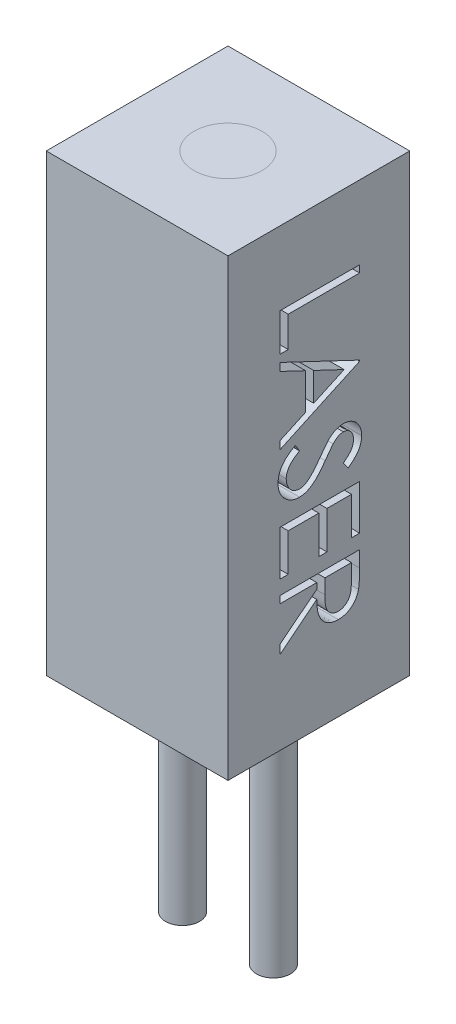
SolidWorks part; units mm, degrees
ref_plane "Front Plane" through (0, 0, 0) normal (0, 0, 1) x (1, 0, 0)
ref_plane "Top Plane" through (0, 0, 0) normal (0, 1, 0) x (1, 0, 0)
ref_plane "Right Plane" through (0, 0, 0) normal (1, 0, 0) x (0, 0, -1)
sketch "Sketch1" plane through (0, 0, 0) normal (0, 0, 1) x (1, 0, 0)
  line L0 (0, -55) -> (0, 55) construction
  line L1 (-4, 20) -> (4, 20)
  line L2 (-4, 20) -> (-4, 0)
  line L3 (-4, 0) -> (4, 0)
  line L4 (4, 20) -> (4, 0)
  line L5 (-4, 20) -> (4, 0) construction
  line L6 (-4, 0) -> (4, 20) construction
  line L7 (55, 0) -> (-55, 0) construction
  point P0 (0, 10)
  dimension "D1" = 20
  dimension "D2" = 8
extrude "Boss-Extrude1" add sketch "Sketch1" along normal blind 8
sketch "Sketch2" plane through (0, 0, 0) normal (0, -1, 0) x (1, 0, 0)
  line L0 (0, -4.4) -> (0, 4.4) construction
  line L1 (4, 8) -> (4, 0) construction
  circle A0 centre (-2, 4) radius 0.75
  circle A1 centre (2, 4) radius 0.75
  point P9 (4, 4)
  dimension "D1" = 1.5
  dimension "D2" = 2
  dimension "D3" = 2
extrude "Boss-Extrude2" add sketch "Sketch2" along normal blind 10
sketch "Sketch3" plane through (0, 20, 0) normal (0, 1, 0) x (1, 0, 0)
  line L0 (0, -4.4) -> (0, 4.4) construction
  line L1 (4, -8) -> (4, 0) construction
  circle A0 centre (0, -4) radius 1.5
  point P7 (4, -4)
  dimension "D1" = 3
split line "Split Line1"
sketch "Sketch4" plane through (4, 0, 0) normal (1, 0, 0) x (0, 0, -1)
  line L0 (-5.7072, 17.2132) -> (-5.7072, 2.7675) construction
  text T0 "LASER"
  point P3 (-5.7072, 9.9903)
extrude "Cut-Extrude1" cut sketch "Sketch4" against normal blind 1
